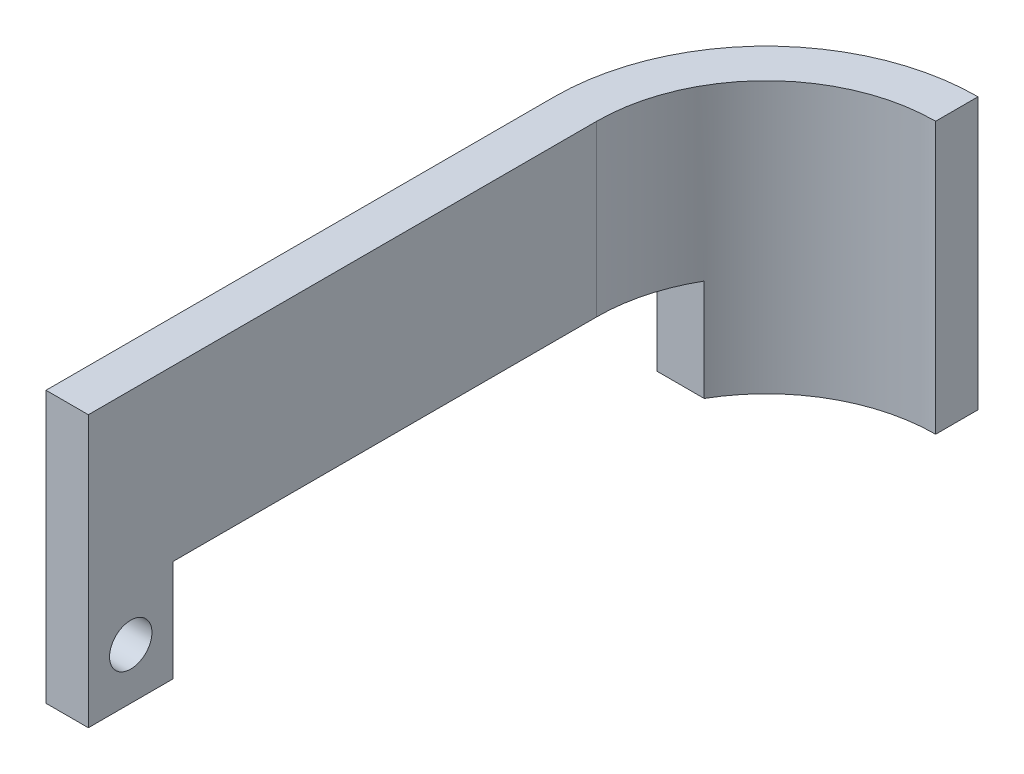
SolidWorks part; units mm, degrees
ref_plane "Front Plane" through (0, 0, 0) normal (0, 0, 1) x (1, 0, 0)
ref_plane "Top Plane" through (0, 0, 0) normal (0, 1, 0) x (1, 0, 0)
ref_plane "Right Plane" through (0, 0, 0) normal (1, 0, 0) x (0, 0, -1)
sketch "Sketch1" plane through (0, 0, 0) normal (0, 1, 0) x (1, 0, 0)
  line L0 (31.75, 101.6) -> (31.75, 107.95)
  line L1 (0, 0) -> (6.35, 0)
  line L2 (0, 0) -> (0, 76.2)
  line L4 (6.35, 0) -> (6.35, 76.2)
  arc A0 (31.75, 107.95) -> (0, 76.2) centre (31.75, 76.2) ccw
  arc A1 (31.75, 101.6) -> (6.35, 76.2) centre (31.75, 76.2) ccw
  dimension "D3" = 63.5
  dimension "D4" = 50.8
  dimension "D1" = 76.2
  dimension "D2" = 6.35
extrude "Boss-Extrude1" add sketch "Sketch1" along normal blind 40.64
sketch "Sketch2" plane through (6.35, 0, 0) normal (1, 0, 0) x (0, 0, -1)
  line L0 (0, 40.64) -> (0, 0) construction
  line L1 (0, 0) -> (76.2, 0) construction
  circle A0 centre (6.35, 7.62) radius 3.175
  dimension "D1" = 6.35
  dimension "D2" = 6.35
  dimension "D3" = 7.62
sketch "Sketch3" plane through (0, 0, 0) normal (1, 0, 0) x (0, 0, -1)
  line L0 (0, 0) -> (76.2, 0) construction
  line L1 (12.7, 0) -> (88.9, 0)
  line L2 (12.7, 0) -> (12.7, 15.24)
  line L3 (12.7, 15.24) -> (88.9, 15.24)
  line L4 (88.9, 0) -> (88.9, 15.24)
  line L5 (0, 40.64) -> (0, 0) construction
  dimension "D1" = 76.2
  dimension "D2" = 15.24
  dimension "D3" = 12.7
extrude "Cut-Extrude1" cut sketch "Sketch2" against normal blind 40.64
extrude "Cut-Extrude2" cut sketch "Sketch3" along normal blind 40.64
